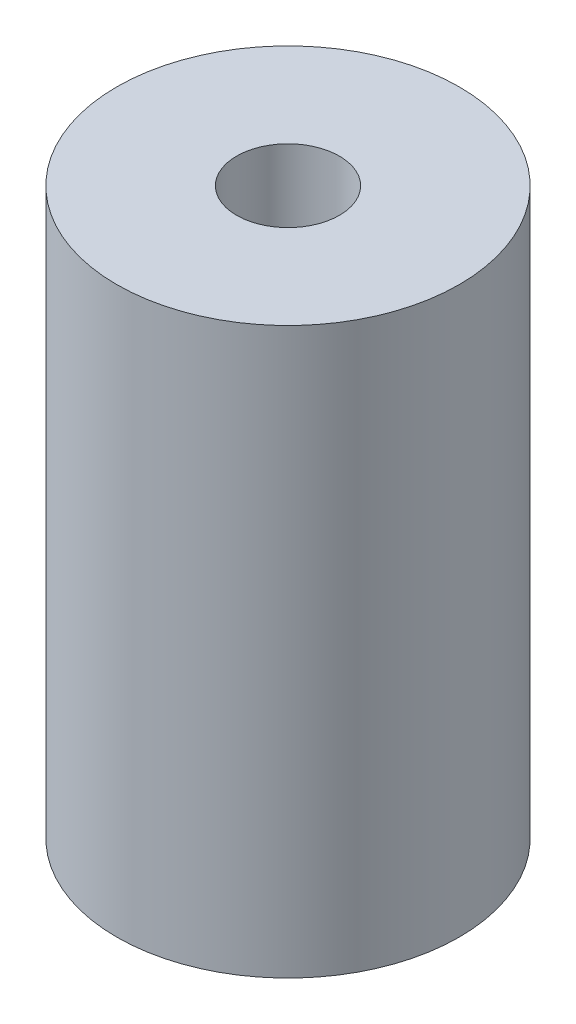
SolidWorks part; units mm, degrees
ref_plane "前视基准面" through (0, 0, 0) normal (0, 0, 1) x (1, 0, 0)
ref_plane "上视基准面" through (0, 0, 0) normal (0, 1, 0) x (1, 0, 0)
ref_plane "右视基准面" through (0, 0, 0) normal (1, 0, 0) x (0, 0, -1)
other "Configuration Table"
sketch "草图1" plane through (0, 0, 0) normal (0, 1, 0) x (1, 0, 0)
  circle A0 centre (0, 0) radius 1.5
  circle A1 centre (0, 0) radius 5
  dimension "D1" = 3
  dimension "D2" = 10
extrude "凸台-拉伸1" add sketch "草图1" along normal blind 16.5
